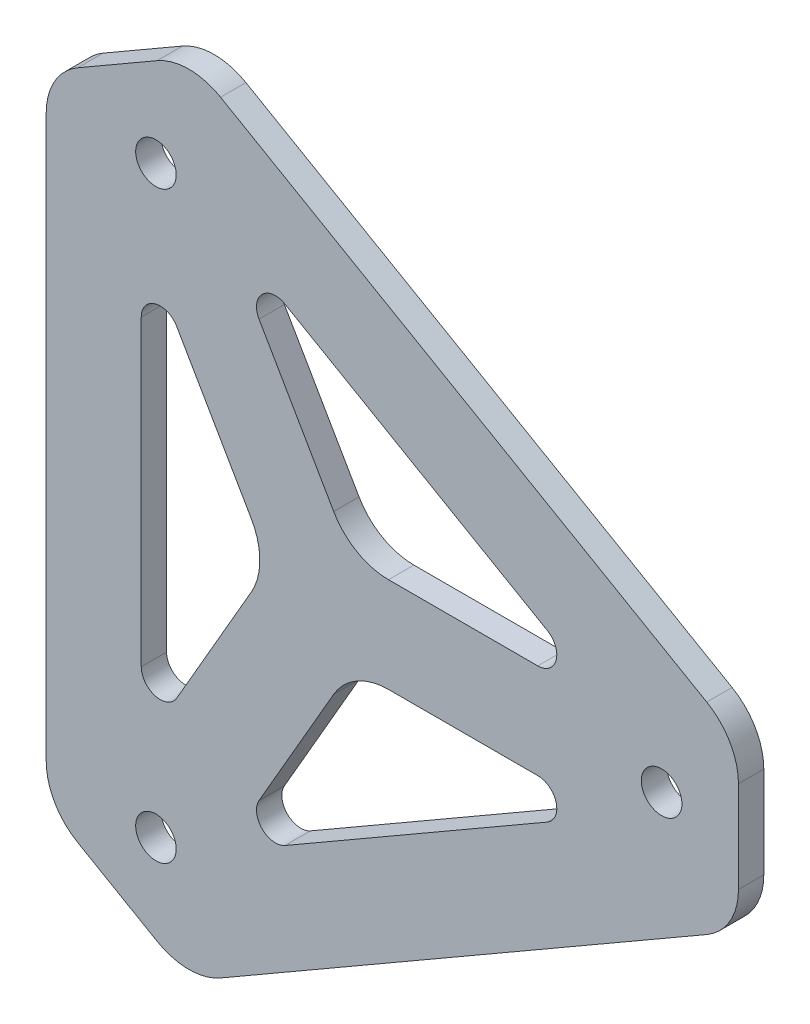
SolidWorks part; units mm, degrees
ref_plane "正面" through (0, 0, 0) normal (0, 0, 1) x (1, 0, 0)
ref_plane "平面" through (0, 0, 0) normal (0, 1, 0) x (1, 0, 0)
ref_plane "右側面" through (0, 0, 0) normal (1, 0, 0) x (0, 0, -1)
sketch "ｽｹｯﾁ1" plane through (0, 0, 0) normal (0, 0, 1) x (1, 0, 0)
  line L0 (-10.7032, 31.5385) -> (-21.9615, 25.0385)
  line L1 (26.6025, 0) -> (-13.3013, 23.0385) construction
  line L2 (-13.3013, 23.0385) -> (-13.3013, -23.0385) construction
  line L3 (-13.3013, -23.0385) -> (26.6025, 0) construction
  line L4 (32.6647, 6.5) -> (-10.7032, 31.5385)
  line L5 (-21.9615, 25.0385) -> (-21.9615, -25.0385)
  line L6 (-10.7032, -31.5385) -> (32.6647, -6.5)
  line L7 (-21.9615, -25.0385) -> (-10.7032, -31.5385)
  line L8 (32.6647, -6.5) -> (32.6647, 6.5)
  circle A0 centre (0, 0) radius 13.3013 construction
  circle A1 centre (-13.3013, 23.0385) radius 1.6
  circle A2 centre (-13.3013, -23.0385) radius 1.6
  circle A3 centre (26.6025, 0) radius 1.6
  circle A4 centre (0, 0) radius 21.9615 construction
  point P10 (43.923, 0)
  point P11 (-21.9615, 38.0385)
  point P12 (-21.9615, -38.0385)
  dimension "D2" = 3.2
  dimension "D3" = 3.2
  dimension "D4" = 3.2
  dimension "D1" = 46.077
  dimension "D5" = 76.077
extrude "ﾎﾞｽ - 押し出し1" add sketch "ｽｹｯﾁ1" along normal blind 2
sketch "ｽｹｯﾁ2" plane through (0, 0, 2) normal (0, 0, 1) x (1, 0, 0)
  line L12 (-12.5824, 21.7933) -> (0, 0)
  line L13 (0, 0) -> (-12.5824, -21.7933)
  line L14 (0, 0) -> (25.1647, 0)
  line L15 (0, -3.75) -> (25.1647, -3.75)
  line L16 (-15.83, 19.9183) -> (-3.2476, -1.875)
  line L17 (-3.2476, 1.875) -> (-15.83, -19.9183)
  line L18 (25.1647, 2.1699) -> (-10.7032, 22.8782)
  line L19 (-10.7032, 22.8782) -> (-14.4615, 20.7083)
  line L20 (-14.4615, 20.7083) -> (-14.4615, -20.7083)
  line L21 (-14.4615, -20.7083) -> (-10.7032, -22.8782)
  line L22 (-10.7032, -22.8782) -> (25.1647, -2.1699)
  line L23 (25.1647, -2.1699) -> (25.1647, 2.1699)
  line L24 (25.1647, 2.1699) -> (-10.7032, 22.8782)
  line L25 (-10.7032, 22.8782) -> (-14.4615, 20.7083)
  line L26 (-14.4615, 20.7083) -> (-14.4615, -20.7083)
  line L27 (-14.4615, -20.7083) -> (-10.7032, -22.8782)
  line L28 (-10.7032, -22.8782) -> (25.1647, -2.1699)
  line L29 (25.1647, -2.1699) -> (25.1647, 2.1699)
  line L30 (0, 3.75) -> (25.1647, 3.75)
  line L31 (-9.3348, 23.6683) -> (3.2476, 1.875)
  line L32 (3.2476, -1.875) -> (-9.3348, -23.6683)
  dimension "D1" = 7.5
  dimension "D2" = 3.75
  dimension "D3" = 3.75
extrude "ｶｯﾄ - 押し出し1" cut sketch "ｽｹｯﾁ2" against normal blind 10 contours L16 L26 L17 | L15 L32 L28 | L24 L31 L30
fillet "ﾌｨﾚｯﾄ1" radius 5 9 edges at (2.1651, 3.75, 1) (2.1651, -3.75, 1) (-4.3301, 0, 1) (32.6647, -6.5, 1) (32.6647, 6.5, 1) (-10.7032, 31.5385, 1) (-21.9615, 25.0385, 1) (-21.9615, -25.0385, 1) (-10.7032, -31.5385, 1)
fillet "ﾌｨﾚｯﾄ2" radius 1.5 6 edges at (-7.9663, -21.2981, 1) (22.4279, -3.75, 1) (-14.4615, -17.5481, 1) (-14.4615, 17.5481, 1) (22.4279, 3.75, 1) (-7.9663, 21.2981, 1)
